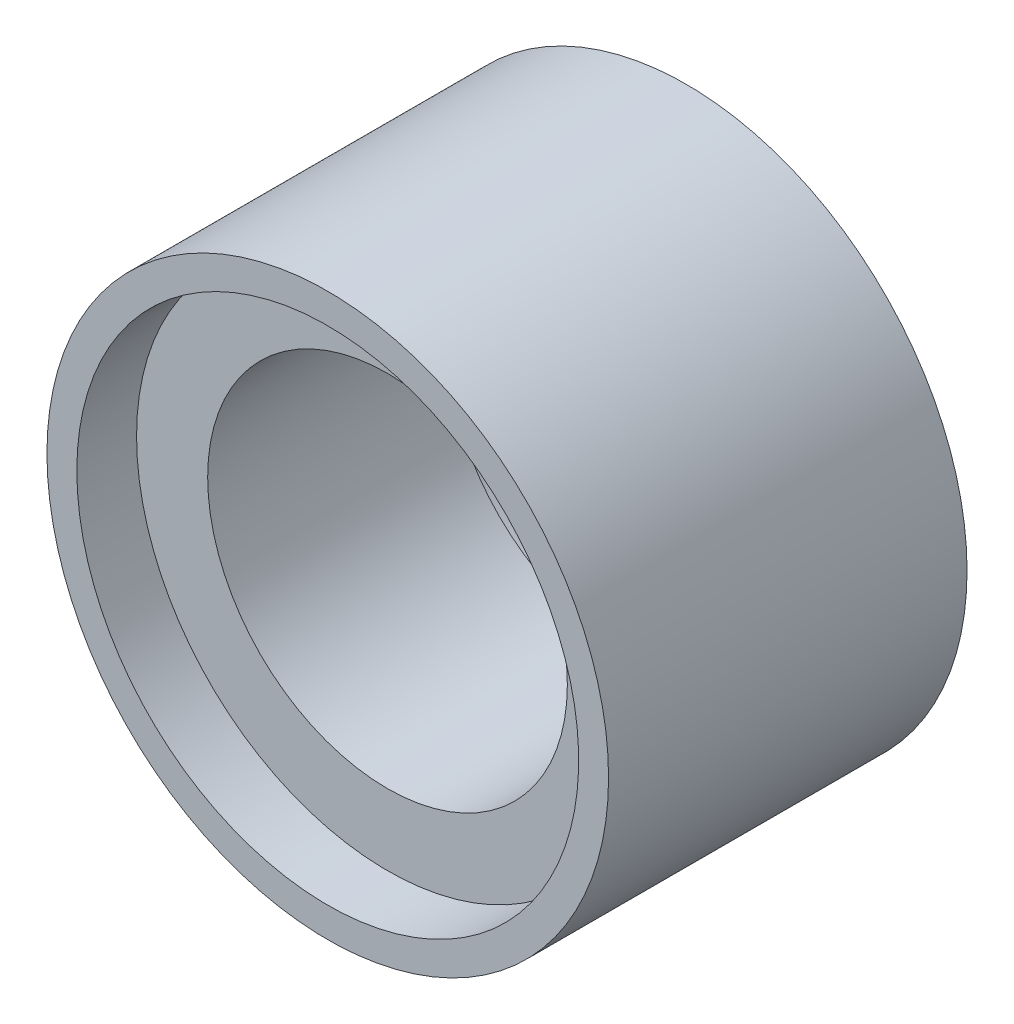
SolidWorks part; units mm, degrees
material "6063-O"
ref_plane "Front Plane" through (0, 0, 0) normal (0, 0, 1) x (1, 0, 0)
ref_plane "Top Plane" through (0, 0, 0) normal (0, 1, 0) x (1, 0, 0)
ref_plane "Right Plane" through (0, 0, 0) normal (1, 0, 0) x (0, 0, -1)
sketch "Sketch1" plane through (0, 0, 0) normal (0, 0, 1) x (1, 0, 0)
  circle A0 centre (0, 0) radius 23.5
  circle A1 centre (0, 0) radius 15.05
  dimension "D1" = 47
  dimension "D2" = 30.1
extrude "Boss-Extrude1" add sketch "Sketch1" along normal mid plane 20
sketch "Sketch2" plane through (0, 0, -10) normal (0, 0, -1) x (-1, 0, 0)
  circle A0 centre (0, 0) radius 21
  circle A1 centre (0, 0) radius 23.5
  dimension "D1" = 47
  dimension "D2" = 42
extrude "Boss-Extrude2" add sketch "Sketch2" along normal blind 5
mirror "Mirror1" about plane through (0, 0, 0) normal (0, 0, 1) of "Boss-Extrude2"
sketch "Sketch3" plane through (0, 0, -10) normal (0, 0, -1) x (-1, 0, 0)
  circle A0 centre (0, 0) radius 21
  circle A1 centre (0, 0) radius 15.05
extrude "Cut-Extrude1" [suppressed] cut sketch "Sketch3" against normal blind 1.8
mirror "Mirror2" [suppressed] about plane through (0, 0, 0) normal (0, 0, 1)
